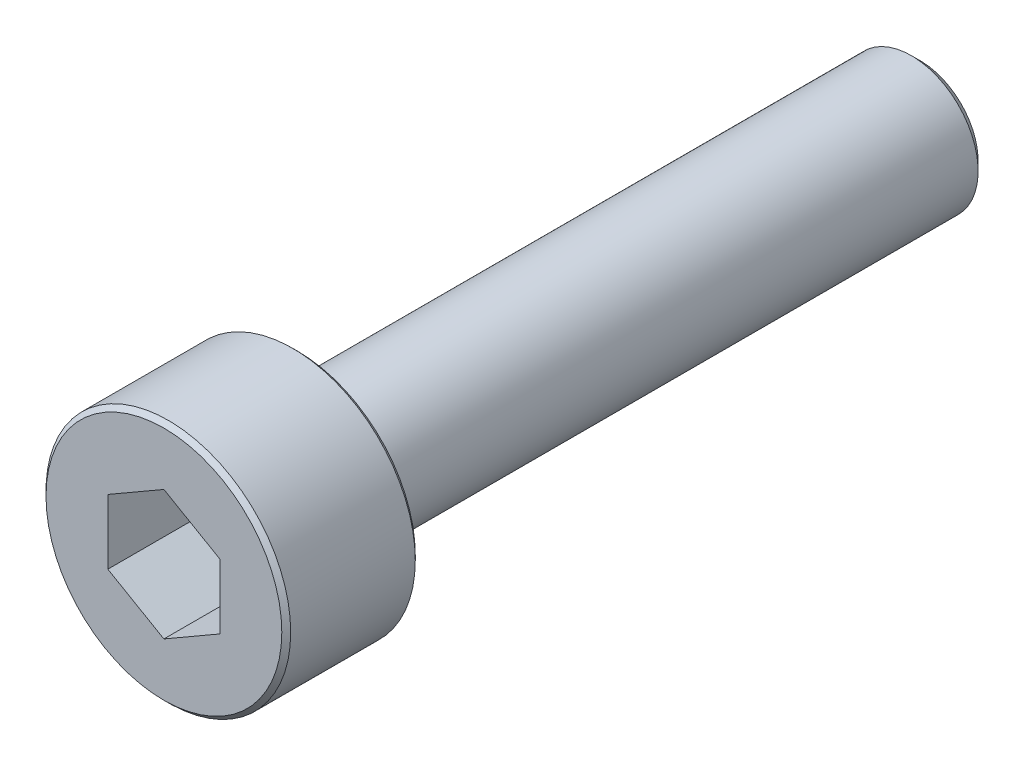
SolidWorks part; units mm, degrees
ref_plane "前视基准面" through (0, 0, 0) normal (0, 0, 1) x (1, 0, 0)
ref_plane "上视基准面" through (0, 0, 0) normal (0, 1, 0) x (1, 0, 0)
ref_plane "右视基准面" through (0, 0, 0) normal (1, 0, 0) x (0, 0, -1)
other "Configuration Table"
sketch "草图1" plane through (0, 0, 0) normal (0, 1, 0) x (1, 0, 0)
  line L0 (2.75, -14) -> (0, -14)
  line L1 (0, -14) -> (0, -17)
  line L2 (0, -17) -> (2.75, -17)
  line L3 (2.75, -17) -> (2.75, -14)
  line L4 (0, -14) -> (0, -17) construction
revolve "旋转1" add sketch "草图1" angle 360 about L4
sketch "草图2" plane through (0, 0, 14) normal (0, 0, -1) x (-1, 0, 0)
  circle A0 centre (0, 0) radius 1.5
extrude "凸台-拉伸1" add sketch "草图2" along normal blind 14
sketch "草图3" plane through (0, 0, 17) normal (0, 0, 1) x (1, 0, 0)
  line L0 (-1.26, -0.7275) -> (0, -1.4549)
  line L1 (0, -1.4549) -> (1.26, -0.7275)
  line L2 (1.26, -0.7275) -> (1.26, 0.7275)
  line L3 (1.26, 0.7275) -> (0, 1.4549)
  line L4 (0, 1.4549) -> (-1.26, 0.7275)
  line L5 (-1.26, 0.7275) -> (-1.26, -0.7275)
extrude "切除-拉伸1" cut sketch "草图3" against normal blind 2.25
chamfer "倒角1" distance 0.1 angle 45 2 edges at (2.75, 0, 14) (2.75, 0, 17)
chamfer "倒角2" distance 0.2 angle 45 1 edges at (-1.5, 0, 0)
